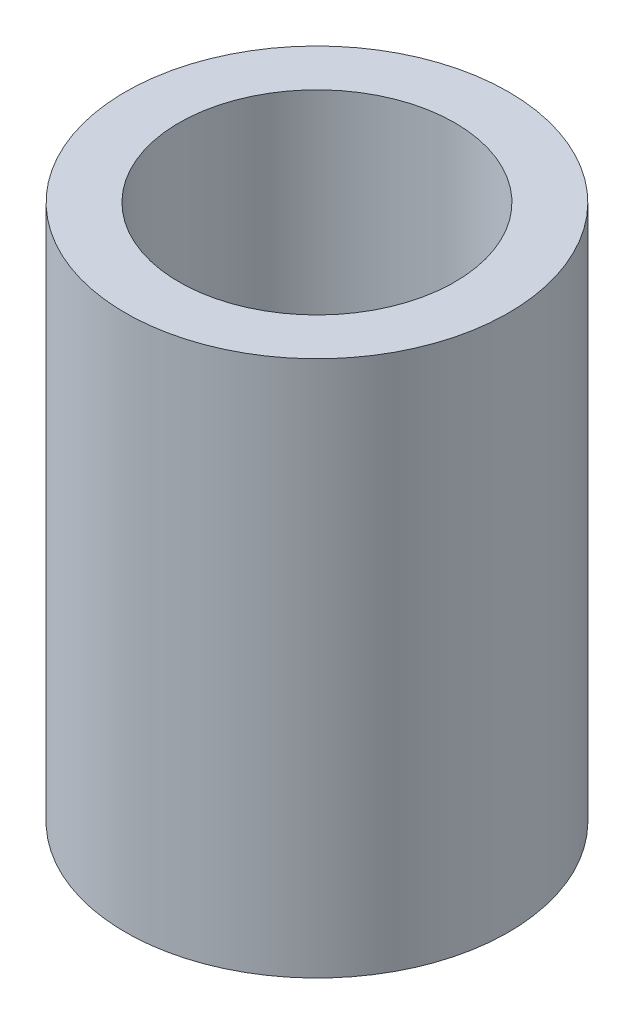
SolidWorks part; units mm, degrees
ref_plane "Front Plane" through (0, 0, 0) normal (0, 0, 1) x (1, 0, 0)
ref_plane "Top Plane" through (0, 0, 0) normal (0, 1, 0) x (1, 0, 0)
ref_plane "Right Plane" through (0, 0, 0) normal (1, 0, 0) x (0, 0, -1)
sketch "Sketch1" plane through (0, 0, 0) normal (0, 0, 1) x (1, 0, 0)
  line L0 (0, 0) -> (0, 36.1586) construction
  line L1 (12.5, 0) -> (12.5, 35)
  line L2 (12.5, 35) -> (9, 35)
  line L3 (9, 35) -> (9, 11)
  line L6 (9, 11) -> (11, 11)
  line L7 (11, 11) -> (11, 0)
  line L8 (11, 0) -> (12.5, 0)
  dimension "D1" = 25
  dimension "D2" = 22
  dimension "D3" = 18
  dimension "D4" = 24
  dimension "D5" = 35
revolve "Revolve1" add sketch "Sketch1" angle 360 about L0
